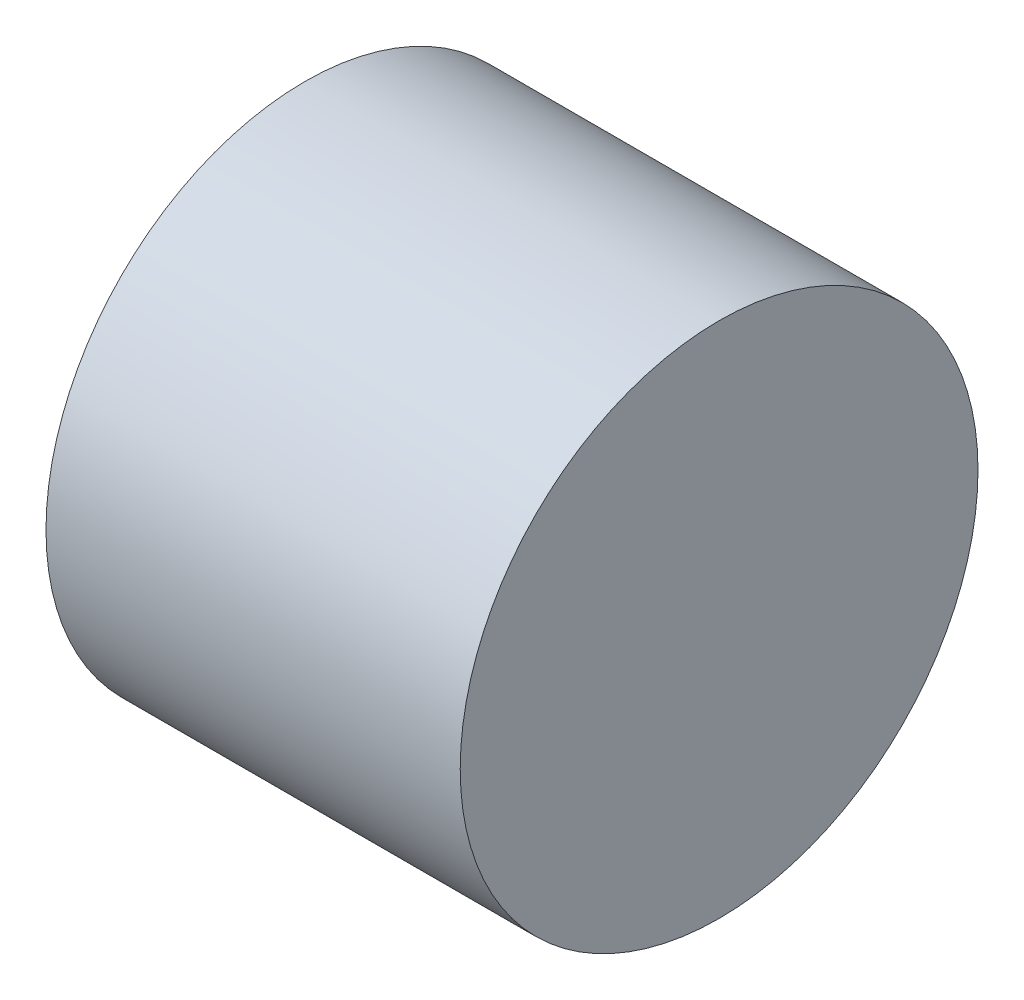
SolidWorks part; units mm, degrees
ref_plane "Ebene vorne" through (0, 0, 0) normal (0, 0, 1) x (1, 0, 0)
ref_plane "Ebene oben" through (0, 0, 0) normal (0, 1, 0) x (1, 0, 0)
ref_plane "Ebene rechts" through (0, 0, 0) normal (1, 0, 0) x (0, 0, -1)
sketch "Skizze2" plane through (0, 0, 0) normal (1, 0, 0) x (0, 0, -1)
  circle A0 centre (0, 0) radius 100
  dimension "D2" = 200
extrude "Aufsatz-Linear austragen1" add sketch "Skizze2" along normal blind 160
